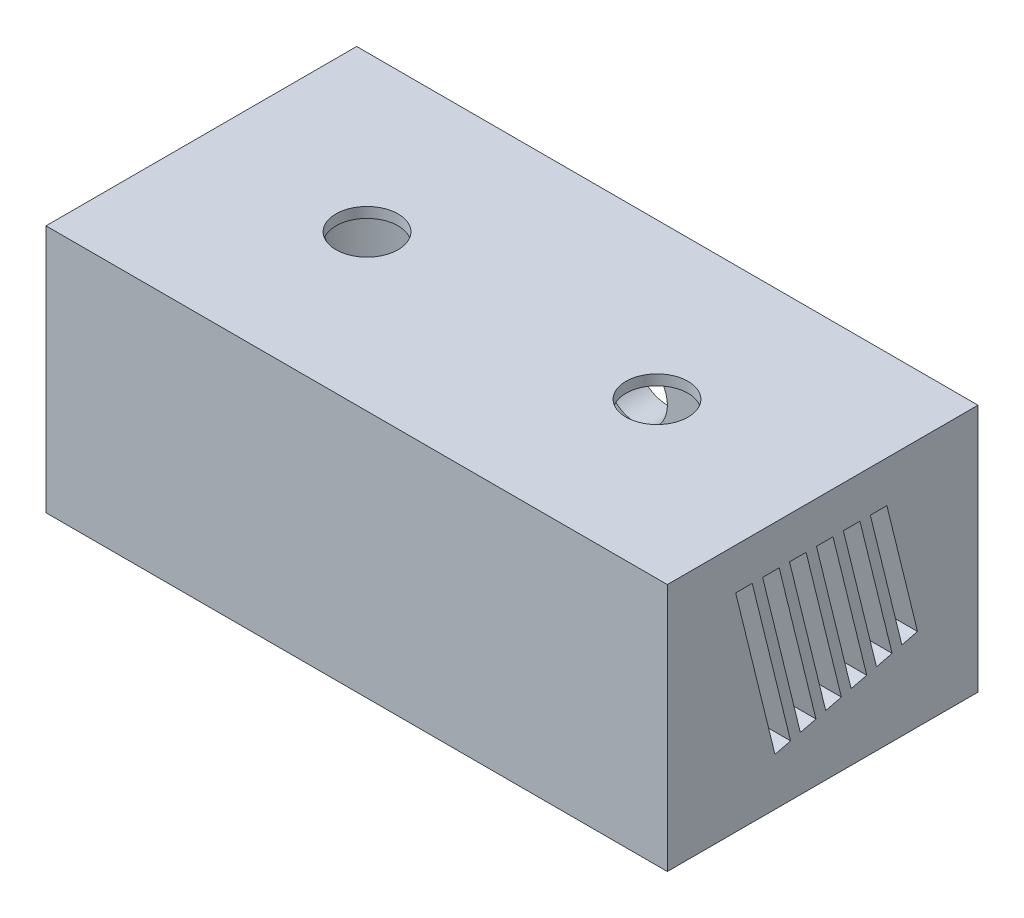
SolidWorks part; units mm, degrees
ref_plane "Front Plane" through (0, 0, 0) normal (0, 0, 1) x (1, 0, 0)
ref_plane "Top Plane" through (0, 0, 0) normal (0, 1, 0) x (1, 0, 0)
ref_plane "Right Plane" through (0, 0, 0) normal (1, 0, 0) x (0, 0, -1)
sketch "Sketch2" plane through (0, 0, 0) normal (0, 1, 0) x (1, 0, 0)
  line L0 (0, 75) -> (0, -75) construction
  line L1 (-150, 75) -> (150, 75)
  line L2 (-150, 75) -> (-150, -75)
  line L3 (-150, -75) -> (150, -75)
  line L4 (150, 75) -> (150, -75)
  line L5 (-150, 75) -> (150, -75) construction
  line L6 (-150, -75) -> (150, 75) construction
  line L7 (-100, 75) -> (-100, -75) construction
  line L8 (100, 75) -> (100, -75) construction
  line L10 (-135, 75) -> (-65, 75) construction
  line L11 (-135, 75) -> (-135, -75) construction
  line L12 (-135, -75) -> (-65, -75) construction
  line L13 (-65, 75) -> (-65, -75) construction
  line L14 (-135, 75) -> (-65, -75) construction
  line L15 (-135, -75) -> (-65, 75) construction
  point P0 (0, 0)
  point P12 (-100, 0)
  dimension "D1" = 150
  dimension "D2" = 300
  dimension "D3" = 100
  dimension "D4" = 100
  dimension "D5" = 70
  dimension "D6" = 150
extrude "Boss-Extrude1" add sketch "Sketch2" along normal blind 120
sketch "Sketch7" plane through (0, 0, 0) normal (0, -1, 0) x (1, 0, 0)
  line L0 (-150, -75) -> (-150, 75) construction
  line L1 (-120, 65) -> (120, 65)
  line L2 (-140, 45) -> (-140, -45)
  line L3 (-120, -65) -> (120, -65)
  line L4 (140, 45) -> (140, -45)
  line L7 (-150, 75) -> (150, 75) construction
  line L8 (150, -75) -> (-150, -75) construction
  line L9 (150, 75) -> (150, -75) construction
  arc A0 (-140, 45) -> (-120, 65) centre (-120, 45) cw
  arc A1 (-140, -45) -> (-120, -65) centre (-120, -45) ccw
  arc A2 (140, -45) -> (120, -65) centre (120, -45) cw
  arc A3 (120, 65) -> (140, 45) centre (120, 45) cw
  point P0 (0, 0)
  dimension "D1" = 10
  dimension "D2" = 10
  dimension "D3" = 20
  dimension "D4" = 20
  dimension "D5" = 20
  dimension "D6" = 10
  dimension "D7" = 10
extrude "Cut-Extrude2" cut sketch "Sketch7" against normal blind 5
sketch "Sketch8" plane through (0, 5, 0) normal (0, -1, 0) x (1, 0, 0)
  line L0 (-91.7157, 60) -> (91.7157, 60)
  line L1 (-135, 16.7157) -> (-135, -16.7157)
  line L2 (-91.7157, -60) -> (91.7157, -60)
  line L3 (135, 16.7157) -> (135, -16.7157)
  line L4 (-140, 45) -> (-140, -45) construction
  line L5 (-120, 65) -> (120, 65) construction
  line L6 (140, 45) -> (140, -45) construction
  line L7 (-120, -65) -> (120, -65) construction
  arc A0 (-135, 16.7157) -> (-91.7157, 60) centre (-91.7157, 16.7157) cw
  arc A1 (-135, -16.7157) -> (-91.7157, -60) centre (-91.7157, -16.7157) ccw
  arc A2 (91.7157, -60) -> (135, -16.7157) centre (91.7157, -16.7157) ccw
  arc A3 (91.7157, 60) -> (135, 16.7157) centre (91.7157, 16.7157) cw
  arc A4 (120, -65) -> (140, -45) centre (120, -45) ccw construction
  dimension "D5" = 40
  dimension "D1" = 5
  dimension "D2" = 5
  dimension "D3" = 5
  dimension "D4" = 5
extrude "Cut-Extrude3" cut sketch "Sketch8" against normal offset from surface (110 mm away) 5 up to face at (0, 120, 0)
sketch "Sketch15" plane through (150, 0, 0) normal (1, 0, 0) x (0, 0, -1)
  line L0 (-75, 120) -> (-75, 0) construction
  line L7 (-42, 100) -> (-23.0297, 23.0202)
  line L9 (-55, 100) -> (55, 100) construction
  line L10 (-75, 120) -> (75, 120) construction
  line L11 (75, 120) -> (75, 0) construction
  line L12 (-55, 100) -> (-35.2854, 20) construction
  line L29 (-35.2854, 20) -> (55, 42.2492) construction
  line L30 (55, 42.2492) -> (40.7684, 100) construction
  line L31 (-45, 0) -> (45, 0) construction
  line L32 (-47, 100) -> (-27.7435, 21.8586) construction
  line L33 (-55, 100) -> (-47, 100) construction
  line L34 (-23.0297, 23.0202) -> (-15.4877, 24.8788)
  line L35 (-15.4877, 24.8788) -> (-34, 100)
  line L36 (-34, 100) -> (-42, 100)
  line L37 (-29, 100) -> (-10.774, 26.0404)
  line L38 (-10.774, 26.0404) -> (-3.232, 27.899)
  line L39 (-3.232, 27.899) -> (-21, 100)
  line L40 (-21, 100) -> (-29, 100)
  line L45 (-16, 100) -> (1.4817, 29.0606)
  line L46 (1.4817, 29.0606) -> (9.0237, 30.9192)
  line L47 (9.0237, 30.9192) -> (-8, 100)
  line L48 (-8, 100) -> (-16, 100)
  line L49 (-3, 100) -> (13.7375, 32.0808)
  line L50 (13.7375, 32.0808) -> (21.2794, 33.9394)
  line L51 (21.2794, 33.9394) -> (5, 100)
  line L52 (5, 100) -> (-3, 100)
  line L57 (10, 100) -> (25.9932, 35.101)
  line L58 (25.9932, 35.101) -> (33.5352, 36.9596)
  line L59 (33.5352, 36.9596) -> (18, 100)
  line L60 (18, 100) -> (10, 100)
  line L61 (23, 100) -> (38.2489, 38.1212)
  line L62 (38.2489, 38.1212) -> (45.7909, 39.9798)
  line L63 (45.7909, 39.9798) -> (31, 100)
  line L64 (31, 100) -> (23, 100)
  line L65 (36, 100) -> (44, 100) construction
  line L66 (44, 100) -> (58.0466, 43) construction
  line L67 (58.0466, 43) -> (50.5046, 41.1414) construction
  line L68 (50.5046, 41.1414) -> (36, 100) construction
  line L69 (-35.2854, 20) -> (-27.7435, 21.8586) construction
  point P16 (-75, 60)
  dimension "D1" = 20
  dimension "D2" = 20
  dimension "D3" = 20
  dimension "D4" = 90
  dimension "D5" = 20
  dimension "D6" = 8
  dimension "D7" = 77
  dimension "D8" = 8
  dimension "D9" = 8
  dimension "D10" = 5
  dimension "D11" = 8
  dimension "D12" = 8
  dimension "D13" = 5
  dimension "D14" = 5
  dimension "D15" = 5
  dimension "D16" = 5
  dimension "D17" = 5
  dimension "D18" = 8
  dimension "D19" = 5
  dimension "D20" = 8
  dimension "D21" = 8
hole_wizard "CBORE for M4 Pan Head Machine Screw1" positions "Sketch13" profile "Sketch14" counterbore size "M4" standard "ANSI Metric"
sketch "Sketch13" plane through (0, 0, 0) normal (0, -1, 0) x (-1, 0, 0)
  line L1 (120, -65) -> (-120, -65) construction
  line L2 (140, -45) -> (140, 45) construction
  point P0 (-128, 53)
  point P2 (128, 53)
  point P4 (128, -53)
  point P6 (-128, -53)
  dimension "D1" = 12
  dimension "D2" = 12
  dimension "D3" = 12
  dimension "D4" = 12
sketch "Sketch14" plane through (128, 0, -53) normal (1, 0, 0) x (0, 0, -1)
  line L0 (0, 0) -> (0, 31.3519)
  line L1 (0, 31.3519) -> (2.25, 30)
  line L2 (2.25, 30) -> (2.25, 3.1)
  line L3 (2.25, 3.1) -> (4.5, 3.1)
  line L5 (4.5, 3.1) -> (4.5, 0.025)
  line L6 (4.5, 0.025) -> (4.525, 0)
  line L7 (4.525, 0) -> (0, 0)
  line L8 (-4.5, 0.025) -> (-4.525, 0) construction
  line L10 (0, 31.3519) -> (-2.25, 30) construction
  line L11 (0, -6.35) -> (0, 107.95) construction
  dimension "Hole Dia." = 4.5
  dimension "Hole Depth" = 30
  dimension "C'Bore Dia." = 9
  dimension "C'Bore Depth" = 3.1
  dimension "Near C'Sink Dia." = 9.05
  dimension "Near C'Sink Angle" = 90
  dimension "Drill Angle" = 118
extrude "Cut-Extrude5" cut sketch "Sketch15" against normal through all
sketch "Sketch17" plane through (0, 0, -75) normal (0, 0, -1) x (-1, 0, 0)
  line L0 (-150, 120) -> (-150, 0) construction
  circle A0 centre (0, 60) radius 15
  point P3 (-150, 60)
  dimension "D1" = 30
extrude "Cut-Extrude6" cut sketch "Sketch17" against normal blind 20
sketch "Sketch3" plane through (0, 120, 0) normal (0, 1, 0) x (1, 0, 0)
  line L0 (0, 75) -> (0, -75) construction
  circle A1 centre (-70, 0) radius 15
  circle A2 centre (70, 0) radius 15
  dimension "D1" = 30
  dimension "50" = 70
extrude "Cut-Extrude1" cut sketch "Sketch3" against normal blind 50
